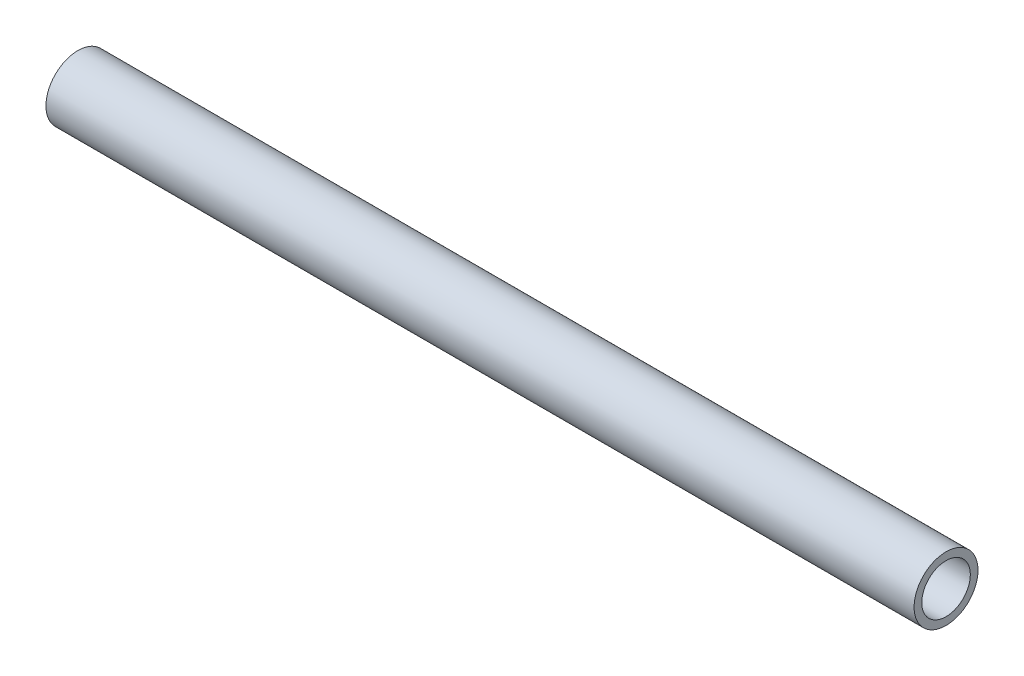
SolidWorks part; units mm, degrees
material "AISI 4130 Steel, annealed at 865C"
ref_plane "Front Plane" through (0, 0, 0) normal (0, 0, 1) x (1, 0, 0)
ref_plane "Top Plane" through (0, 0, 0) normal (0, 1, 0) x (1, 0, 0)
ref_plane "Right Plane" through (0, 0, 0) normal (1, 0, 0) x (0, 0, -1)
sketch "Sketch1" plane through (0, 0, 0) normal (1, 0, 0) x (0, 0, -1)
  circle A0 centre (0, 0) radius 12.7
  circle A1 centre (0, 0) radius 9.652
  dimension "D1" = 25.4
  dimension "D2" = 19.304
extrude "Boss-Extrude1" add sketch "Sketch1" along normal blind 345
